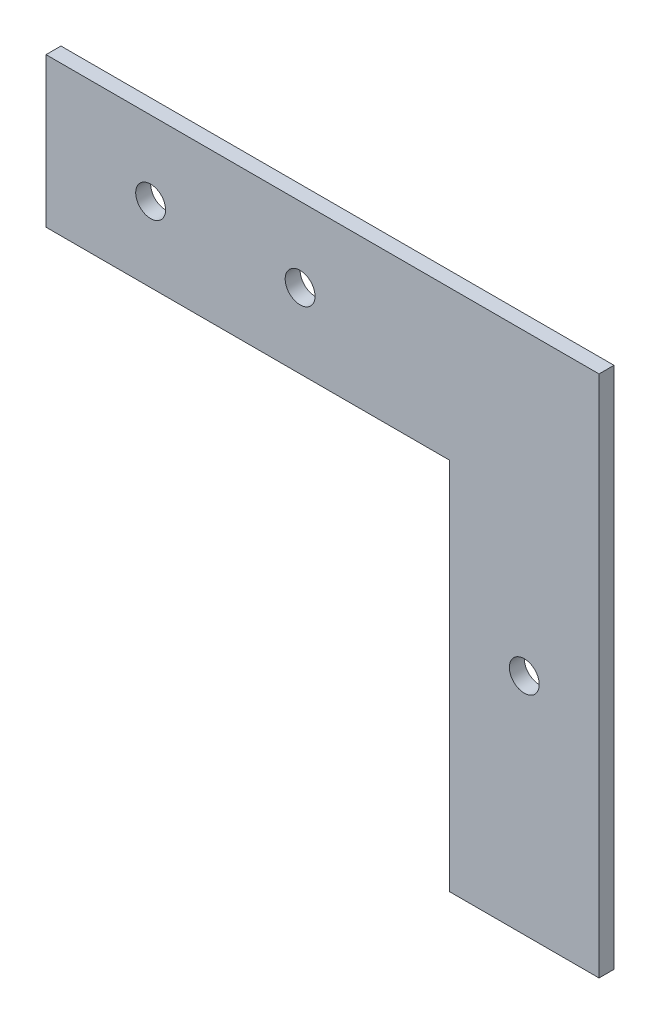
SolidWorks part; units mm, degrees
ref_plane "前视基准面" through (0, 0, 0) normal (0, 0, 1) x (1, 0, 0)
ref_plane "上视基准面" through (0, 0, 0) normal (0, 1, 0) x (1, 0, 0)
ref_plane "右视基准面" through (0, 0, 0) normal (1, 0, 0) x (0, 0, -1)
sketch "草图1" plane through (0, 0, 0) normal (0, 0, 1) x (1, 0, 0)
  line L0 (-55.6857, 27.5603) -> (-55.6857, 7.5603)
  line L1 (-55.6857, 7.5603) -> (-1.6857, 7.5603)
  line L2 (-1.6857, 7.5603) -> (-1.6857, -42.4397)
  line L3 (-1.6857, -42.4397) -> (18.3143, -42.4397)
  line L4 (18.3143, -42.4397) -> (18.3143, 27.5603)
  line L5 (-55.6857, 27.5603) -> (18.3143, 27.5603)
  circle A0 centre (8.3143, -12.4397) radius 2
  circle A1 centre (-21.6857, 17.5603) radius 2
  circle A2 centre (-41.6857, 17.5603) radius 2
  point P14 (-46.3769, 18.271)
  point P15 (-41.0979, 15.6487)
  point P16 (6.315, -12.3855)
  dimension "D5" = 4
  dimension "D6" = 4
  dimension "D7" = 4
  dimension "D1" = 70
  dimension "D2" = 74
  dimension "D3" = 54
  dimension "D4" = 20
  dimension "D8" = 20
  dimension "D9" = 14
  dimension "D10" = 10
  dimension "D11" = 30
  dimension "D12" = 10
extrude "凸台-拉伸1" add sketch "草图1" along normal blind 2
